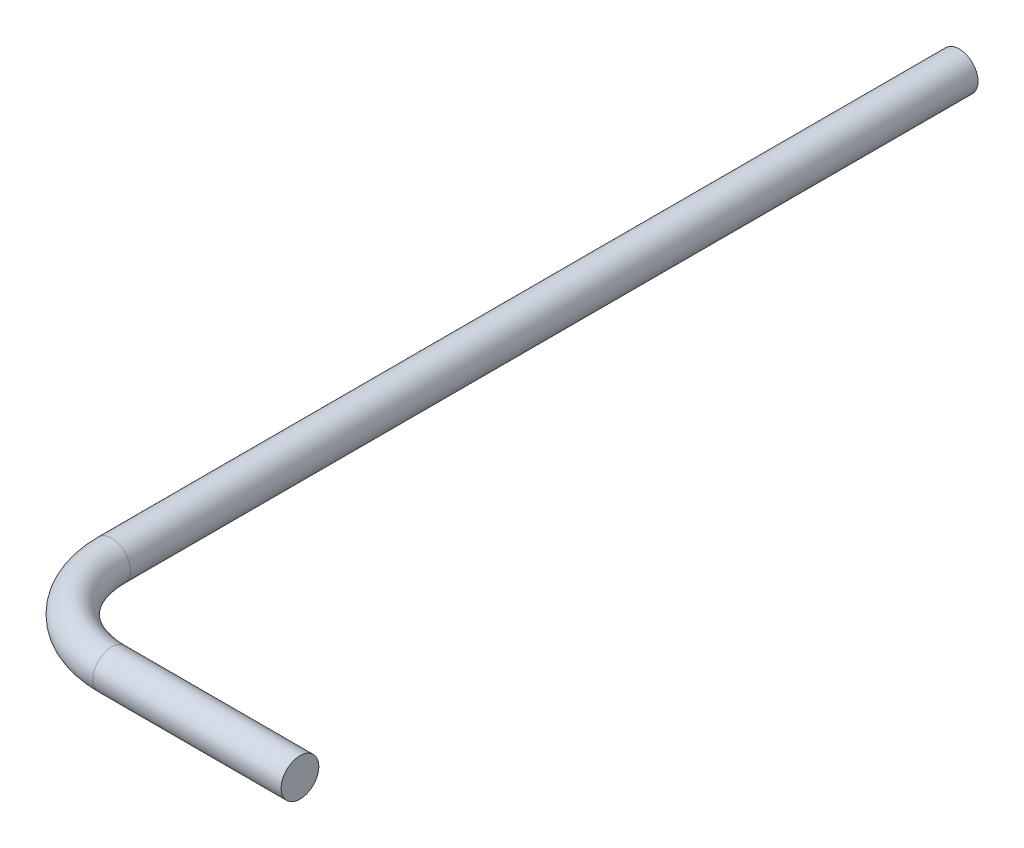
SolidWorks part; units mm, degrees
ref_plane "Front Plane" through (0, 0, 0) normal (0, 0, 1) x (1, 0, 0)
ref_plane "Top Plane" through (0, 0, 0) normal (0, 1, 0) x (1, 0, 0)
ref_plane "Right Plane" through (0, 0, 0) normal (1, 0, 0) x (0, 0, -1)
sketch "Sketch2" plane through (0, 0, 0) normal (0, 1, 0) x (1, 0, 0)
  line L0 (0, 0) -> (-20, 0)
  line L1 (-30, 10) -> (-30, 100)
  arc A0 (-20, 0) -> (-30, 10) centre (-20, 10) cw
  point P6 (-30, 0)
  dimension "D3" = 10
  dimension "D1" = 30
  dimension "D2" = 100
sweep "Sweep1" add path "Sketch2" circular profile diameter 4 parameters "D3"=4
